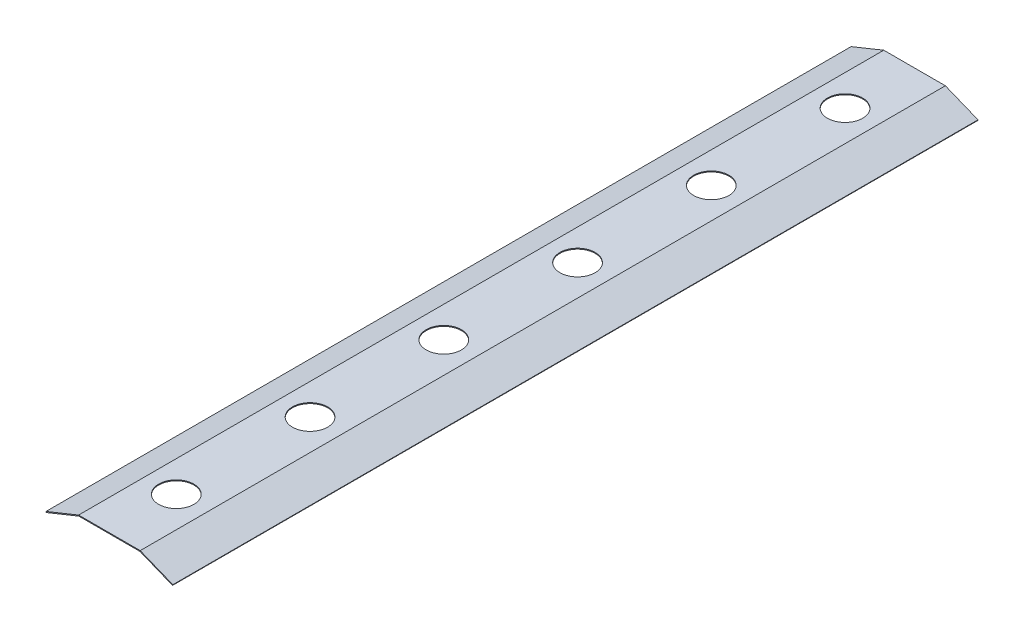
SolidWorks part; units mm, degrees
material "PE Low Density Film"
ref_plane "Front Plane" through (0, 0, 0) normal (0, 0, 1) x (1, 0, 0)
ref_plane "Top Plane" through (0, 0, 0) normal (0, 1, 0) x (1, 0, 0)
ref_plane "Right Plane" through (0, 0, 0) normal (1, 0, 0) x (0, 0, -1)
sketch "Sketch1" plane through (0, 0, 0) normal (0, 0, 1) x (1, 0, 0)
  line L0 (-35, 0) -> (35, 0)
  line L1 (-35, 0) -> (-72.0874, -14.9843)
  line L2 (35, 0) -> (72.0874, -14.9843)
  line L3 (-34.8056, -1) -> (-71.7127, -15.9114)
  line L4 (-34.8056, -1) -> (34.8056, -1)
  line L5 (34.8056, -1) -> (71.7127, -15.9114)
  line L6 (-72.0874, -14.9843) -> (-71.7127, -15.9114)
  line L8 (72.0874, -14.9843) -> (71.7127, -15.9114)
  point P4 (0, 0)
  dimension "D1" = 158
  dimension "D3" = 70
  dimension "D2" = 40
  dimension "D4" = 158
  dimension "D5" = 40
  dimension "D6" = 1
extrude "Boss-Extrude1" add sketch "Sketch1" against normal blind 915
sketch "Sketch2" plane through (0, 0, 0) normal (0, 1, 0) x (1, 0, 0)
  circle A0 centre (0, 76) radius 20
  circle A12 centre (0, 228) radius 20
  circle A13 centre (0, 380) radius 20
  circle A14 centre (0, 532) radius 20
  circle A15 centre (0, 684) radius 20
  circle A16 centre (0, 836) radius 20
extrude "Cut-Extrude1" cut sketch "Sketch2" against normal blind 1000
